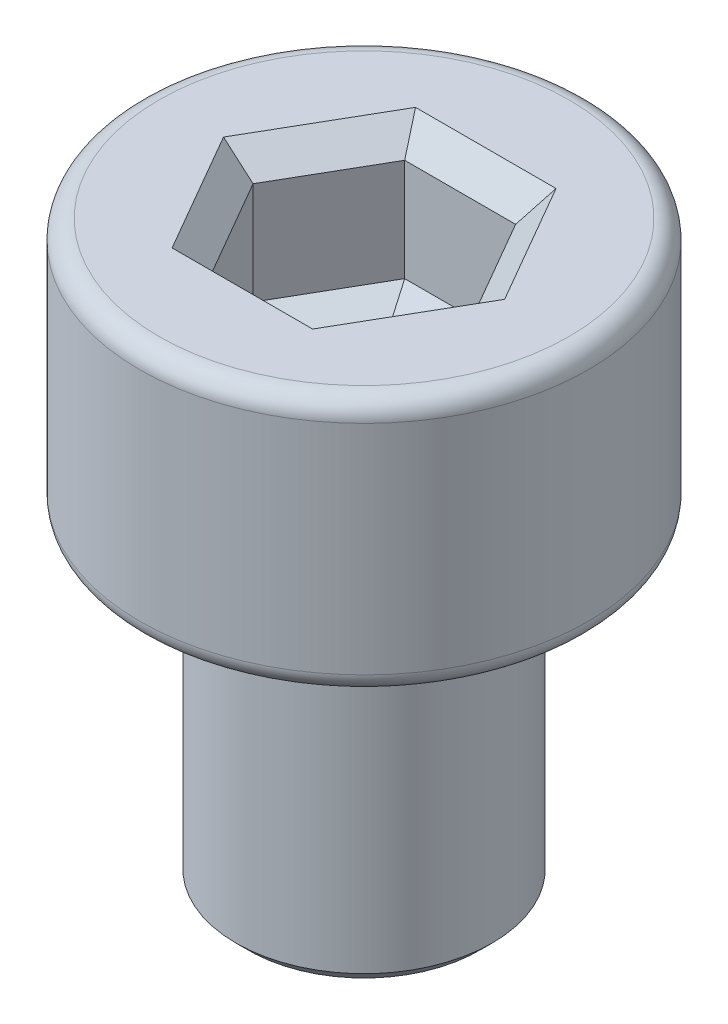
SolidWorks part; units mm, degrees
material "AISI 1020"
ref_plane "Front Plane" through (0, 0, 0) normal (0, 0, 1) x (1, 0, 0)
ref_plane "Top Plane" through (0, 0, 0) normal (0, 1, 0) x (1, 0, 0)
ref_plane "Right Plane" through (0, 0, 0) normal (1, 0, 0) x (0, 0, -1)
sketch "Sketch1" plane through (0, 0, 0) normal (0, 1, 0) x (1, 0, 0)
  circle A0 centre (0, 0) radius 3.5
  dimension "D1" = 7
extrude "Boss-Extrude1" add sketch "Sketch1" along normal blind 4
sketch "Sketch2" plane through (0, 4, 0) normal (0, 1, 0) x (1, 0, 0)
  line L1 (1.7321, 0) -> (0.866, 1.5)
  line L2 (0.866, 1.5) -> (-0.866, 1.5)
  line L3 (-0.866, 1.5) -> (-1.7321, 0)
  line L4 (-1.7321, 0) -> (-0.866, -1.5)
  line L5 (-0.866, -1.5) -> (0.866, -1.5)
  line L6 (0.866, -1.5) -> (1.7321, 0)
  circle A0 centre (0, 0) radius 1.5 construction
  dimension "D1" = 3
extrude "Cut-Extrude1" cut sketch "Sketch2" against normal blind 2
sketch "Sketch5" plane through (0, 2, 0) normal (0, 1, 0) x (1, 0, 0)
  line L6 (0.866, -1.5) -> (1.7321, 0)
  line L7 (1.7321, 0) -> (0.866, 1.5)
  line L8 (0.866, 1.5) -> (-0.866, 1.5)
  line L9 (-0.866, 1.5) -> (-1.7321, 0)
  line L10 (-1.7321, 0) -> (-0.866, -1.5)
  line L11 (-0.866, -1.5) -> (0.866, -1.5)
  line L12 (0.866, -1.5) -> (1.7321, 0)
  line L13 (1.7321, 0) -> (0.866, 1.5)
  line L14 (0.866, 1.5) -> (-0.866, 1.5)
  line L15 (-0.866, 1.5) -> (-1.7321, 0)
  line L16 (-1.7321, 0) -> (-0.866, -1.5)
  line L17 (-0.866, -1.5) -> (0.866, -1.5)
  dimension "D1" = 0
extrude "Cut-Extrude2" cut sketch "Sketch5" against normal blind 1 draft 70
sketch "Sketch6" plane through (0, 0, 0) normal (0, -1, 0) x (1, 0, 0)
  circle A0 centre (0, 0) radius 2
  dimension "D1" = 4
extrude "Boss-Extrude2" add sketch "Sketch6" along normal blind 5
chamfer "Chamfer1" distance 0.4 angle 45 6 edges at (0, 4, 1.5) (-1.299, 4, 0.75) (-1.299, 4, -0.75) (0, 4, -1.5) (1.299, 4, -0.75) (1.299, 4, 0.75)
fillet "Fillet1" radius 0.3 2 edges at (0, 0, 3.5) (0, 4, 3.5)
fillet "Fillet2" radius 0.2 1 edges at (0, 0, -2)
thread "Thread1" pitch 0.7 start angle 0, offset 0.4, length 0, pitch 0.7, diameter 4
ref_plane "Plane1" through (2, -5.4, 0) normal (0, 0, 1) x (1, 0, 0)
sketch "Thread Profile1" plane through (2, -5.4, 0) normal (0, 0, 1) x (1, 0, 0)
  line L0 (0, 0) -> (0, 0.7) construction
  line L11 (0, 0) -> (0, 0.6125)
  line L12 (0, 0.6125) -> (-0.3789, 0.3937)
  line L13 (-0.3789, 0.3937) -> (-0.3789, 0.2187)
  line L15 (-0.3789, 0.2187) -> (0, 0)
  line L17 (-0.3789, 0.3062) -> (0, 0.3062) construction
  point P2 (0, 0)
  dimension "Pitch" = 0.7
  dimension "Profile_Angle" = 60
  dimension "Profile_Land" = 0.175
  dimension "Profile_Height" = 0.3789
chamfer "Chamfer2" distance 0.2 angle 45 1 edges at (0, -5, -2)
